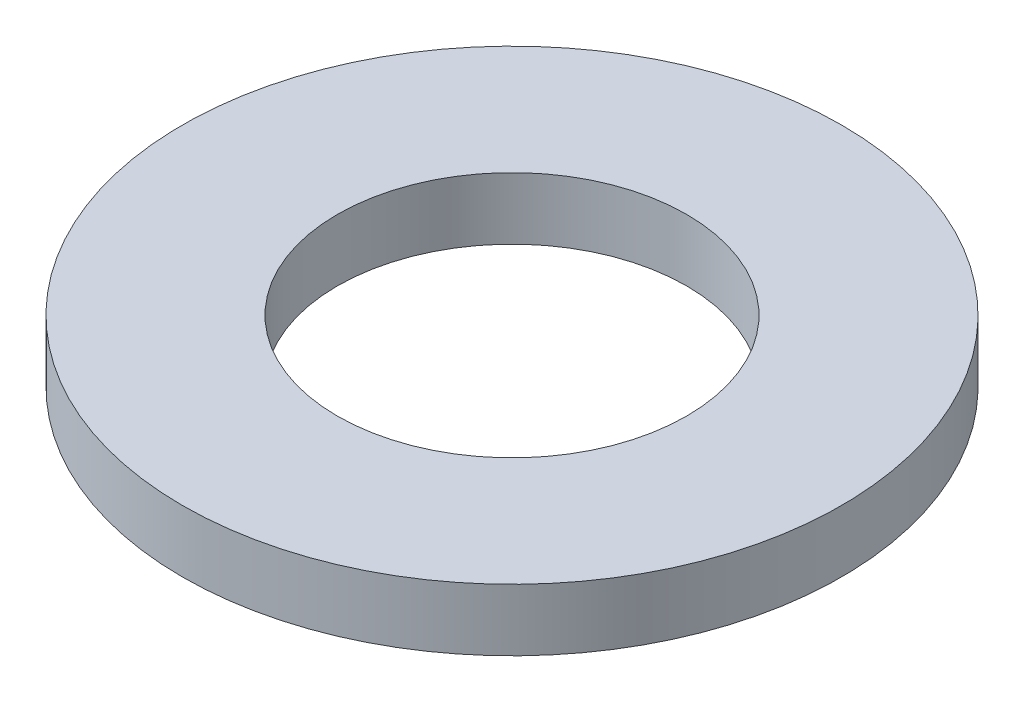
SolidWorks part; units mm, degrees
ref_plane "Front Plane" through (0, 0, 0) normal (0, 0, 1) x (1, 0, 0)
ref_plane "Top Plane" through (0, 0, 0) normal (0, 1, 0) x (1, 0, 0)
ref_plane "Right Plane" through (0, 0, 0) normal (1, 0, 0) x (0, 0, -1)
sketch "Sketch1" plane through (0, 0, 0) normal (0, 1, 0) x (1, 0, 0)
  circle A0 centre (0, 0) radius 2.65
  circle A1 centre (0, 0) radius 5
  dimension "D1" = 10
  dimension "D2" = 5.3
extrude "Boss-Extrude1" add sketch "Sketch1" along normal blind 0.94
